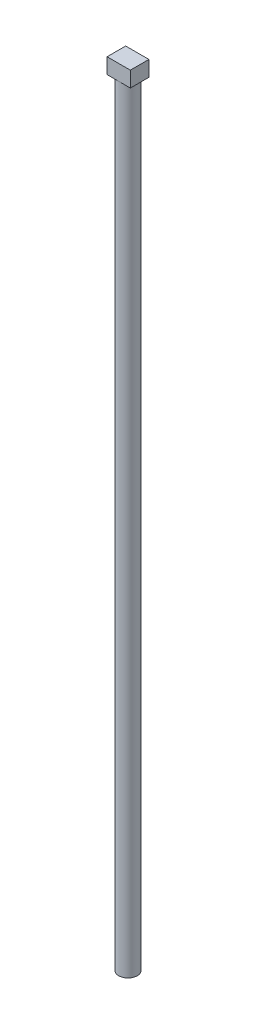
SolidWorks part; units mm, degrees
ref_plane "前视基准面" through (0, 0, 0) normal (0, 0, 1) x (1, 0, 0)
ref_plane "上视基准面" through (0, 0, 0) normal (0, 1, 0) x (1, 0, 0)
ref_plane "右视基准面" through (0, 0, 0) normal (1, 0, 0) x (0, 0, -1)
sketch "草图2" plane through (0, 0, 0) normal (0, 1, 0) x (1, 0, 0)
  circle A0 centre (0, 0) radius 1.2
  circle A1 centre (0, 0) radius 0.7
  dimension "D1" = 2.4
  dimension "D2" = 1.4
extrude "凸台-拉伸1" add sketch "草图2" along normal blind 100
sketch "草图3" plane through (0, 100, 0) normal (0, 1, 0) x (1, 0, 0)
  line L1 (-1.5, -1.2) -> (1.5, -1.2)
  line L2 (-1.5, -1.2) -> (-1.5, 1.2)
  line L3 (-1.5, 1.2) -> (1.5, 1.2)
  line L4 (1.5, -1.2) -> (1.5, 1.2)
  line L5 (-1.5, -1.2) -> (1.5, 1.2) construction
  line L6 (-1.5, 1.2) -> (1.5, -1.2) construction
  point P0 (0, 0)
  dimension "D1" = 2.4
  dimension "D2" = 3
extrude "凸台-拉伸2" add sketch "草图3" along normal blind 2
